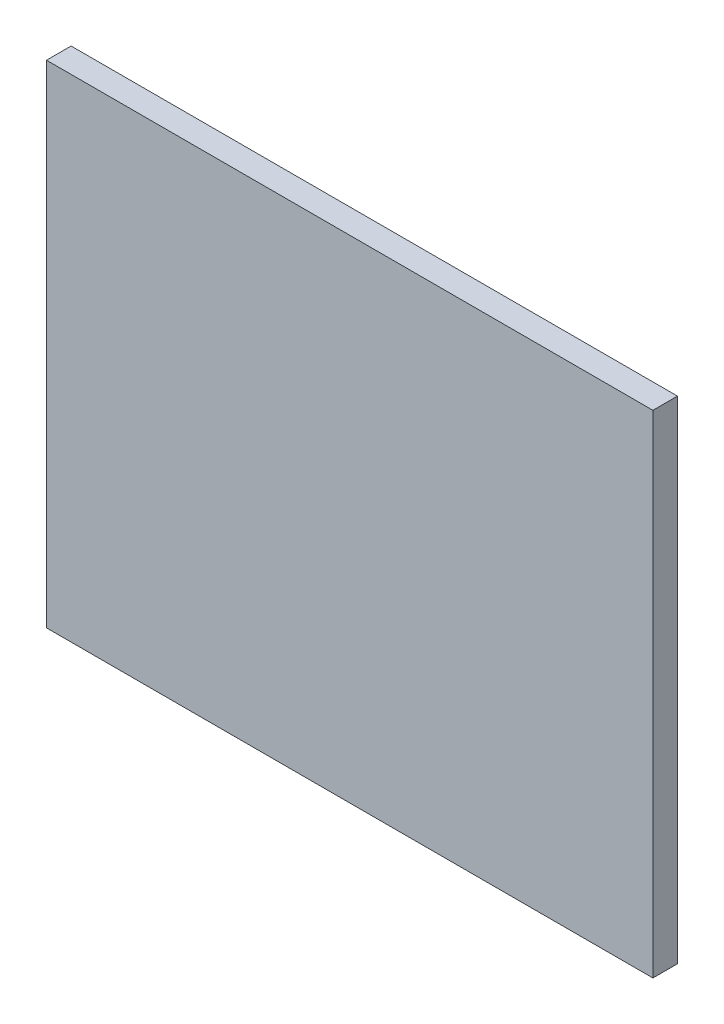
SolidWorks part; units mm, degrees
material "Alliage 1060"
ref_plane "Plan de dessus" through (0, 0, 0) normal (0, 0, 1) x (1, 0, 0)
ref_plane "Plan de droite" through (0, 0, 0) normal (0, 1, 0) x (1, 0, 0)
ref_plane "Plan de face" through (0, 0, 0) normal (1, 0, 0) x (0, 0, -1)
sketch "Esquisse1" plane through (0, 0, 0) normal (0, 0, 1) x (1, 0, 0)
  line L1 (0, 0) -> (74, 0)
  line L2 (0, 0) -> (0, 60)
  line L3 (0, 60) -> (74, 60)
  line L4 (74, 0) -> (74, 60)
  dimension "D1" = 74
  dimension "D2" = 60
extrude "Boss.-Extru.1" add sketch "Esquisse1" along normal blind 3
